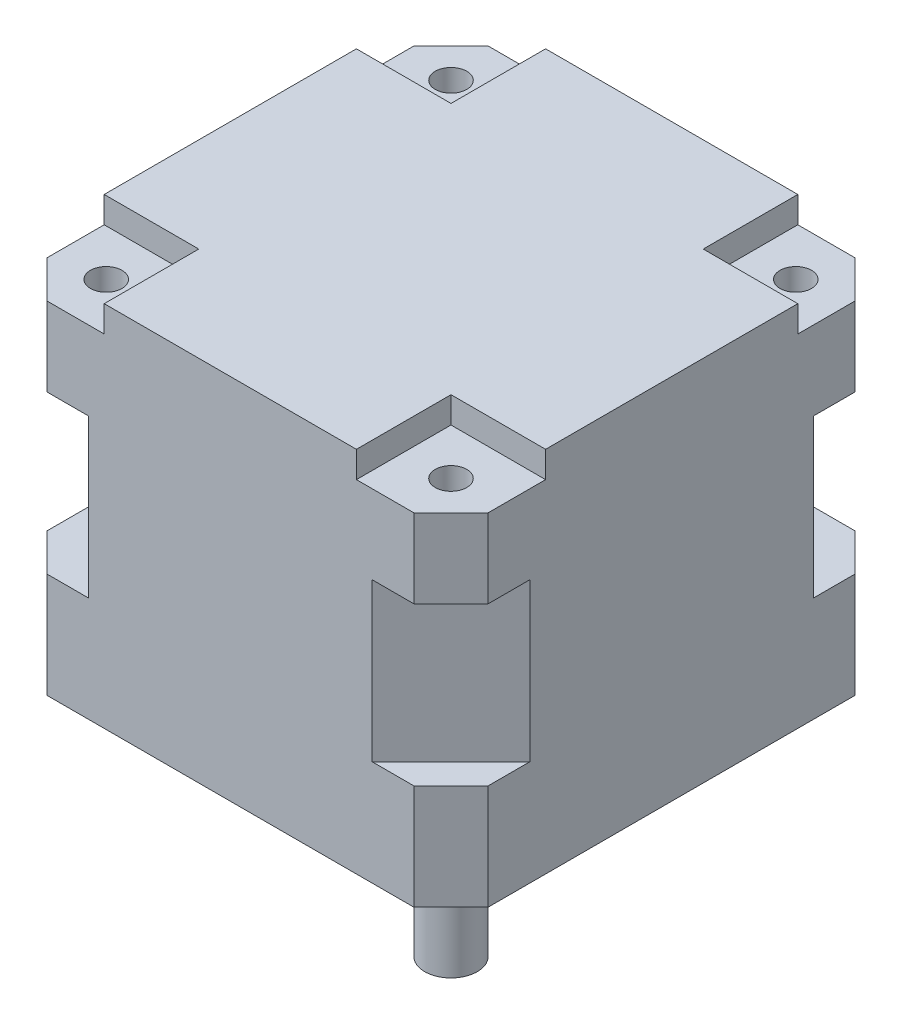
SolidWorks part; units mm, degrees
ref_plane "Front Plane" through (0, 0, 0) normal (0, 0, 1) x (1, 0, 0)
ref_plane "Top Plane" through (0, 0, 0) normal (0, 1, 0) x (1, 0, 0)
ref_plane "Right Plane" through (0, 0, 0) normal (1, 0, 0) x (0, 0, -1)
sketch "Sketch1" plane through (0, 0, 0) normal (0, 1, 0) x (1, 0, 0)
  line L0 (0, 21) -> (0, -21.4443) construction
  line L1 (-20.775, 0) -> (37.4508, 0) construction
  line L2 (-17.4645, 21) -> (17.4645, 21)
  line L3 (21, 17.4645) -> (21, -17.4645)
  line L4 (19.2322, 19.2322) -> (0, 0) construction
  line L5 (17.4645, 21) -> (21, 17.4645)
  line L6 (-17.4645, 21) -> (-21, 17.4645)
  line L7 (-21, 17.4645) -> (-21, -17.4645)
  line L8 (17.4645, -21) -> (21, -17.4645)
  line L9 (-17.4645, -21) -> (17.4645, -21)
  line L10 (-17.4645, -21) -> (-21, -17.4645)
  point P11 (19.2322, 19.2322)
  point P15 (21, 0)
  point P18 (-21, 0)
  dimension "D1" = 21
  dimension "D2" = 21
  dimension "D3" = 2.5
extrude "Boss-Extrude1" add sketch "Sketch1" along normal blind 10
sketch "Sketch2" plane through (0, 10, 0) normal (0, 1, 0) x (1, 0, 0)
  line L0 (0, 21) -> (0, -21) construction
  line L1 (17.4645, 21) -> (-17.4645, 21) construction
  line L2 (-17.4645, -21) -> (17.4645, -21) construction
  line L3 (-21, 0) -> (21, 0) construction
  line L4 (-21, 17.4645) -> (-21, -17.4645) construction
  line L5 (21, -17.4645) -> (21, 17.4645) construction
  line L6 (-13.5, 21) -> (13.5, 21)
  line L7 (21, -13.5) -> (21, 13.5)
  line L8 (13.5, 21) -> (21, 13.5)
  line L9 (-13.5, 21) -> (-21, 13.5)
  line L10 (-21, -13.5) -> (-21, 13.5)
  line L11 (13.5, -21) -> (21, -13.5)
  line L12 (-13.5, -21) -> (13.5, -21)
  line L13 (-13.5, -21) -> (-21, -13.5)
  dimension "D1" = 13.5
  dimension "D2" = 13.5
extrude "Boss-Extrude2" add sketch "Sketch2" along normal blind 15
sketch "Sketch3" plane through (0, 25, 0) normal (0, 1, 0) x (1, 0, 0)
  line L0 (0, 21) -> (0, -21) construction
  line L1 (13.5, 21) -> (-13.5, 21) construction
  line L2 (-13.5, -21) -> (13.5, -21) construction
  line L3 (-21, 0) -> (21, 0) construction
  line L4 (-21, 13.5) -> (-21, -13.5) construction
  line L5 (21, -13.5) -> (21, 13.5) construction
  line L6 (-17.4645, 21) -> (17.4645, 21)
  line L7 (17.4645, 21) -> (21, 17.4645)
  line L8 (21, 17.4645) -> (21, -17.4645)
  line L9 (-21, 17.4645) -> (-21, -17.4645)
  line L10 (-17.4645, 21) -> (-21, 17.4645)
  line L11 (17.4645, -21) -> (21, -17.4645)
  line L12 (-17.4645, -21) -> (17.4645, -21)
  line L13 (-17.4645, -21) -> (-21, -17.4645)
extrude "Boss-Extrude3" add sketch "Sketch3" along normal blind 10
sketch "Sketch4" plane through (0, 35, 0) normal (0, 1, 0) x (1, 0, 0)
  line L0 (0, 21) -> (0, -21) construction
  line L1 (17.4645, 21) -> (-17.4645, 21) construction
  line L2 (-17.4645, -21) -> (17.4645, -21) construction
  line L3 (-21, 0) -> (21, 0) construction
  line L4 (-21, 17.4645) -> (-21, -17.4645) construction
  line L5 (21, -17.4645) -> (21, 17.4645) construction
  line L6 (-12, 12) -> (-21, 12)
  line L7 (-12, 21) -> (-12, 12)
  line L8 (12, 21) -> (12, 12)
  line L9 (12, 12) -> (21, 12)
  line L10 (12, 21) -> (17.4645, 21)
  line L11 (17.4645, 21) -> (21, 17.4645)
  line L12 (21, 17.4645) -> (21, 12)
  line L13 (-12, 21) -> (-17.4645, 21)
  line L14 (-17.4645, 21) -> (-21, 17.4645)
  line L15 (-21, 17.4645) -> (-21, 12)
  line L16 (12, -12) -> (21, -12)
  line L17 (12, -21) -> (12, -12)
  line L18 (12, -21) -> (17.4645, -21)
  line L19 (17.4645, -21) -> (21, -17.4645)
  line L20 (21, -17.4645) -> (21, -12)
  line L21 (-12, -21) -> (-12, -12)
  line L22 (-12, -21) -> (-17.4645, -21)
  line L23 (-17.4645, -21) -> (-21, -17.4645)
  line L24 (-21, -17.4645) -> (-21, -12)
  line L25 (-12, -12) -> (-21, -12)
  dimension "D1" = 12
  dimension "D2" = 12
extrude "Cut-Extrude1" cut sketch "Sketch4" against normal blind 2.5
sketch "Sketch5" plane through (0, 32.5, 0) normal (0, 1, 0) x (1, 0, 0)
  line L0 (19.2322, 19.2322) -> (-19.2322, -19.2322) construction
  line L1 (21, 17.4645) -> (17.4645, 21) construction
  line L2 (-21, -17.4645) -> (-17.4645, -21) construction
  line L3 (-19.2322, 19.2322) -> (19.2322, -19.2322) construction
  line L4 (-17.4645, 21) -> (-21, 17.4645) construction
  line L5 (17.4645, -21) -> (21, -17.4645) construction
  line L6 (0, 21) -> (0, -21) construction
  line L7 (12, 21) -> (-12, 21) construction
  line L8 (-12, -21) -> (12, -21) construction
  line L9 (-21, 0) -> (21, 0) construction
  line L10 (-21, 12) -> (-21, -12) construction
  line L11 (21, -12) -> (21, 12) construction
  circle A0 centre (16.4038, 16.4038) radius 1.5
  circle A1 centre (-16.4038, 16.4038) radius 1.5
  circle A2 centre (-16.4038, -16.4038) radius 1.5
  circle A3 centre (16.4038, -16.4038) radius 1.5
  dimension "D1" = 3
  dimension "D2" = 4
extrude "Cut-Extrude2" cut sketch "Sketch5" against normal blind 3
sketch "Sketch6" plane through (0, 0, 0) normal (0, -1, 0) x (1, 0, 0)
  line L0 (0, -21) -> (0, 21) construction
  line L1 (17.4645, -21) -> (-17.4645, -21) construction
  line L2 (-17.4645, 21) -> (17.4645, 21) construction
  line L3 (-19.2322, -19.2322) -> (19.2322, 19.2322) construction
  line L4 (-17.4645, -21) -> (-21, -17.4645) construction
  line L5 (17.4645, 21) -> (21, 17.4645) construction
  line L6 (21, 0) -> (-21, 0) construction
  line L7 (21, 17.4645) -> (21, -17.4645) construction
  line L8 (-21, -17.4645) -> (-21, 17.4645) construction
  circle A0 centre (0, 0) radius 16
  circle A1 centre (-16.4038, -16.4038) radius 1.5
  circle A2 centre (16.4038, -16.4038) radius 1.5
  circle A3 centre (-16.4038, 16.4038) radius 1.5
  circle A4 centre (16.4038, 16.4038) radius 1.5
  dimension "D1" = 32
  dimension "D2" = 3
  dimension "D3" = 4
extrude "Cut-Extrude3" cut sketch "Sketch6" against normal blind 2
sketch "Sketch7" plane through (0, 2, 0) normal (0, -1, 0) x (1, 0, 0)
  circle A0 centre (0, 0) radius 10
  dimension "D1" = 20
extrude "Boss-Extrude4" add sketch "Sketch7" along normal blind 2.3
sketch "Sketch8" plane through (0, -0.3, 0) normal (0, -1, 0) x (1, 0, 0)
  circle A0 centre (0, 0) radius 2.5
  dimension "D1" = 5
extrude "Boss-Extrude5" add sketch "Sketch8" along normal blind 23
